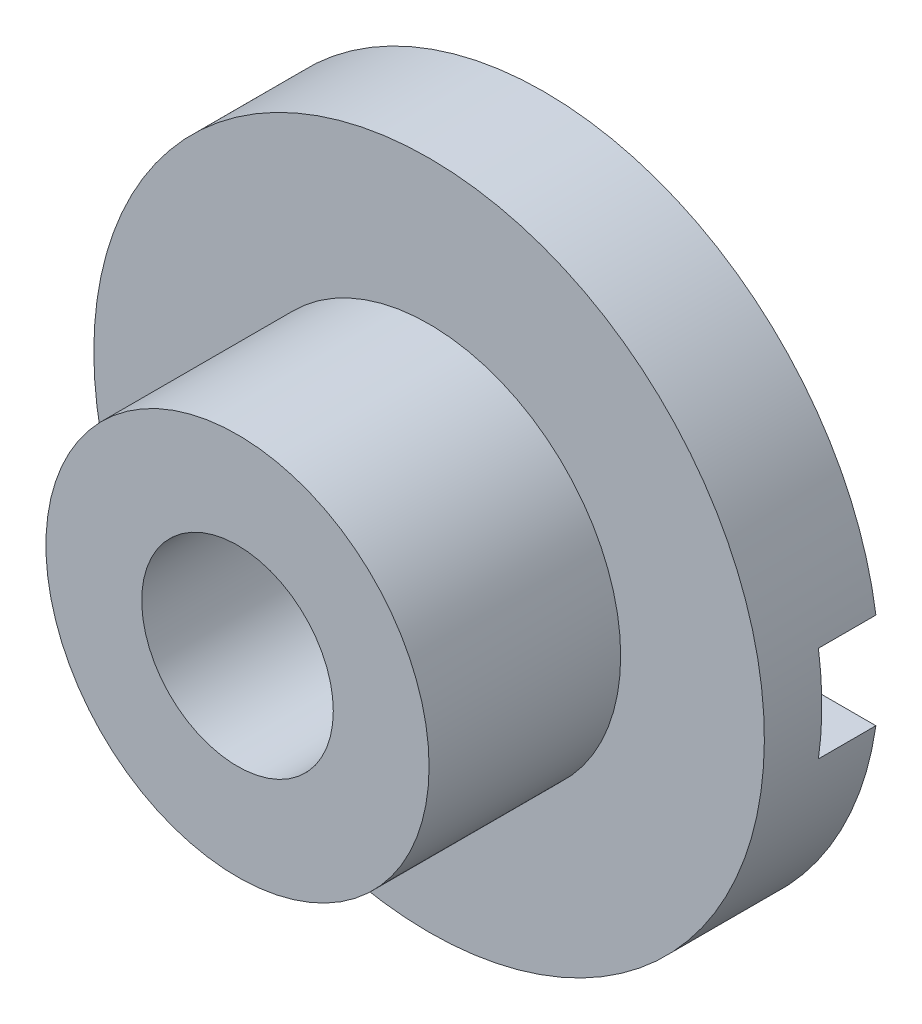
SolidWorks part; units mm, degrees
ref_plane "Front Plane" through (0, 0, 0) normal (0, 0, 1) x (1, 0, 0)
ref_plane "Top Plane" through (0, 0, 0) normal (0, 1, 0) x (1, 0, 0)
ref_plane "Right Plane" through (0, 0, 0) normal (1, 0, 0) x (0, 0, -1)
sketch "Sketch1" plane through (0, 0, 0) normal (0, 0, 1) x (1, 0, 0)
  circle A1 centre (0, 0) radius 3.5
  circle A2 centre (0, 0) radius 7
  dimension "D1" = 7
  dimension "D2" = 14
extrude "Boss-Extrude1" add sketch "Sketch1" along normal blind 7
sketch "Sketch2" plane through (0, 0, 0) normal (0, 0, -1) x (-1, 0, 0)
  circle A0 centre (0, 0) radius 12.25
  dimension "D1" = 24.5
extrude "Boss-Extrude2" add sketch "Sketch2" along normal blind 4.2
sketch "Sketch3" plane through (0, 0, -4.2) normal (0, 0, -1) x (-1, 0, 0)
  line L1 (-12.1244, 1.75) -> (12.1244, 1.75)
  line L3 (-12.1244, -1.75) -> (12.1244, -1.75)
  line L5 (-12.1244, 1.75) -> (12.1244, -1.75) construction
  line L6 (-12.1244, -1.75) -> (12.1244, 1.75) construction
  circle A0 centre (0, 0) radius 12.25 construction
  arc A1 (-12.1244, 1.75) -> (-12.1244, -1.75) centre (0, 0) ccw
  arc A2 (12.1244, -1.75) -> (12.1244, 1.75) centre (0, 0) ccw
  point P0 (0, 0)
  dimension "D1" = 3.5
extrude "Cut-Extrude1" cut sketch "Sketch3" against normal offset from surface (2.1 mm away) 2.1 up to face at (7, 0, 0)
sketch "Sketch4" plane through (0, 0, 0) normal (0, 0, 1) x (1, 0, 0)
  circle A1 centre (0, 0) radius 3.5
  circle A2 centre (0, 0) radius 3.5
  dimension "D1" = 0
extrude "Cut-Extrude2" cut sketch "Sketch4" against normal blind 2.1
